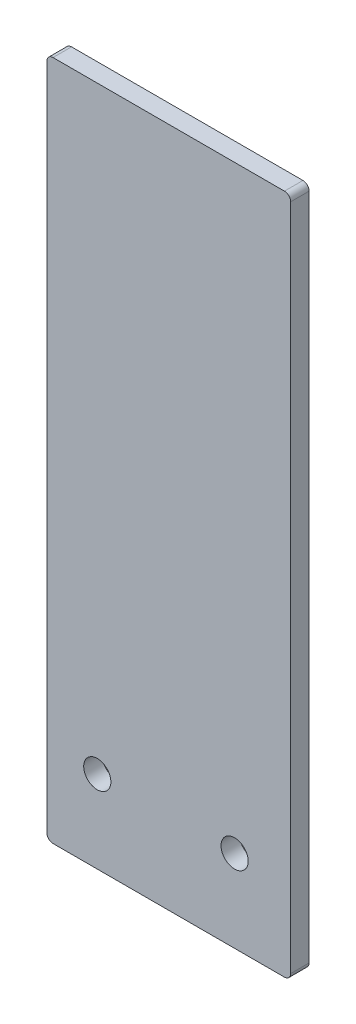
SolidWorks part; units mm, degrees
ref_plane "Plan de face" through (0, 0, 0) normal (0, 0, 1) x (1, 0, 0)
ref_plane "Plan de dessus" through (0, 0, 0) normal (0, 1, 0) x (1, 0, 0)
ref_plane "Plan de droite" through (0, 0, 0) normal (1, 0, 0) x (0, 0, -1)
sketch "Esquisse2" plane through (0, 0, 0) normal (0, 0, 1) x (1, 0, 0)
  line L5 (32.2618, -158.4909) -> (32.2618, -212.6409)
  line L6 (32.7618, -213.1409) -> (51.5121, -213.1409)
  line L7 (52.0121, -158.4909) -> (52.0121, -212.6409)
  line L8 (32.7618, -157.9909) -> (51.5121, -157.9909)
  circle A0 centre (36.3474, -206.4766) radius 1.1
  circle A1 centre (47.4726, -206.4766) radius 1.1
  arc A2 (32.2618, -158.4909) -> (32.7618, -157.9909) centre (32.7618, -158.4909) cw
  arc A3 (52.0121, -158.4909) -> (51.5121, -157.9909) centre (51.5121, -158.4909) ccw
  arc A4 (51.5121, -213.1409) -> (52.0121, -212.6409) centre (51.5121, -212.6409) ccw
  arc A5 (32.2618, -212.6409) -> (32.7618, -213.1409) centre (32.7618, -212.6409) ccw
  dimension "D2" = 0.5
extrude "Boss.-Extru.1" add sketch "Esquisse2" along normal blind 1.5
